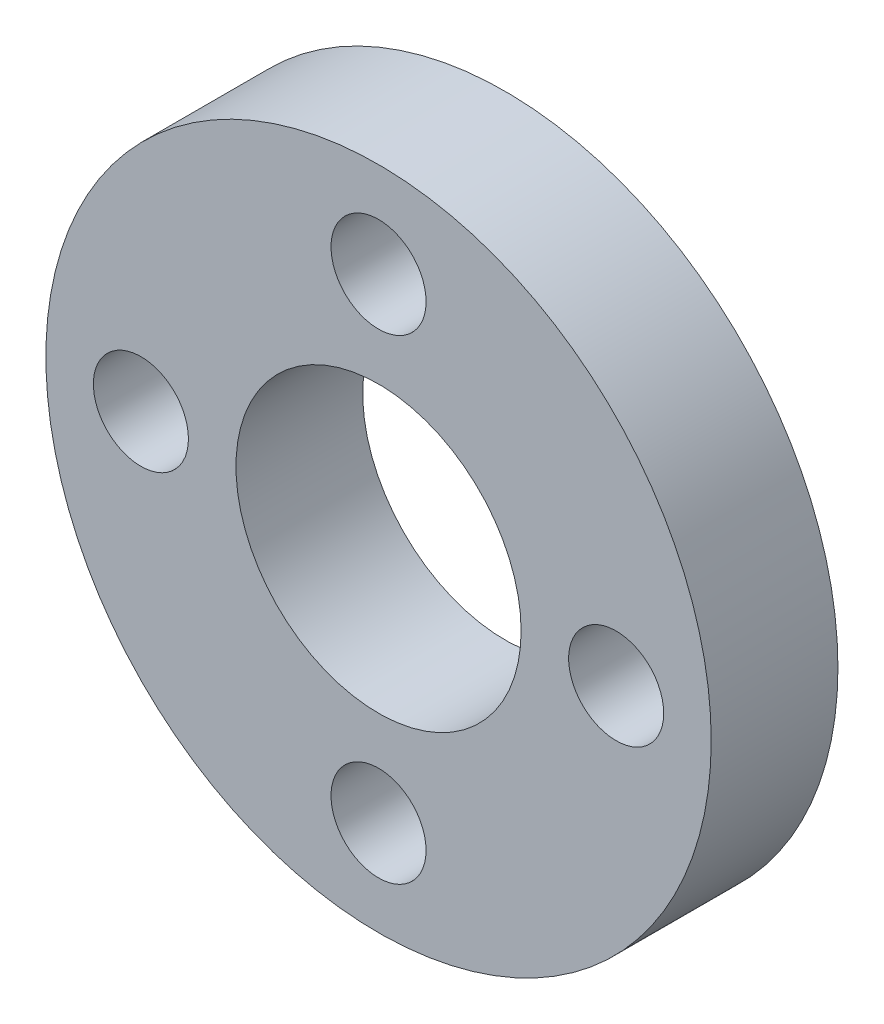
SolidWorks part; units mm, degrees
material "Acrylic (Medium-high impact)"
ref_plane "Front Plane" through (0, 0, 0) normal (0, 0, 1) x (1, 0, 0)
ref_plane "Top Plane" through (0, 0, 0) normal (0, 1, 0) x (1, 0, 0)
ref_plane "Right Plane" through (0, 0, 0) normal (1, 0, 0) x (0, 0, -1)
sketch "Model" plane through (0, 0, 0) normal (0, 0, 1) x (1, 0, 0)
  circle A0 centre (0, 0) radius 7.5 construction
  circle A235 centre (-7.5, 0) radius 1.5
  circle A236 centre (0, 7.5) radius 1.5
  circle A237 centre (7.5, 0) radius 1.5
  circle A238 centre (0, -7.5) radius 1.5
  circle A239 centre (0, 0) radius 4.5
  circle A240 centre (0, 0) radius 10.5
  dimension "D3" = 15
  dimension "D4" = 3
  dimension "D1" = 21
  dimension "D2" = 9
other "AlignGroup1"
other "AlignGroup2"
other "AlignGroup3"
other "AlignGroup4"
extrude "Boss-Extrude1" add sketch "Model" along normal blind 4
